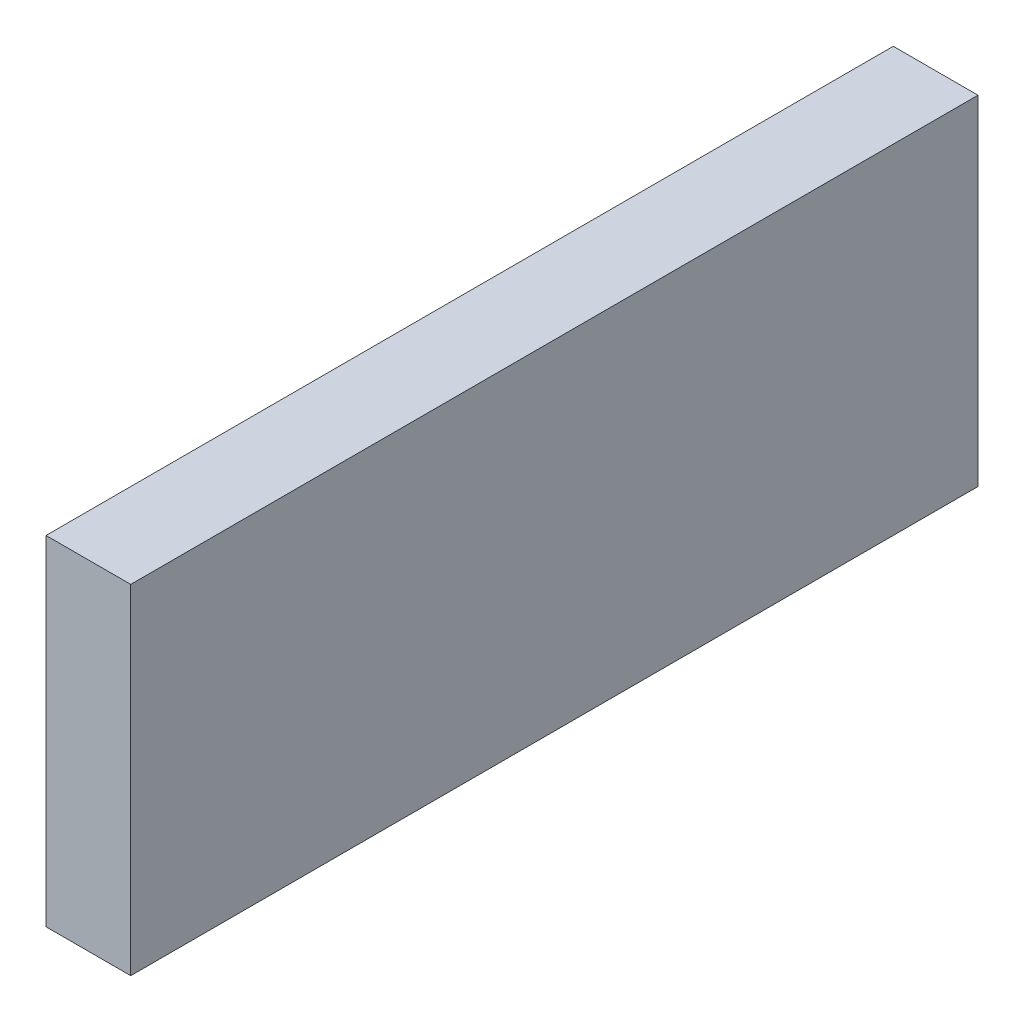
SolidWorks part; units mm, degrees
ref_plane "Front Plane" through (0, 0, 0) normal (0, 0, 1) x (1, 0, 0)
ref_plane "Top Plane" through (0, 0, 0) normal (0, 1, 0) x (1, 0, 0)
ref_plane "Right Plane" through (0, 0, 0) normal (1, 0, 0) x (0, 0, -1)
sketch "Sketch1" plane through (0, 0, 0) normal (0, 1, 0) x (1, 0, 0)
  line L1 (0, 0) -> (9.525, 0)
  line L2 (0, 0) -> (0, 95.25)
  line L3 (0, 95.25) -> (9.525, 95.25)
  line L4 (9.525, 0) -> (9.525, 95.25)
  dimension "D1" = 95.25
  dimension "D2" = 9.525
extrude "Boss-Extrude1" add sketch "Sketch1" along normal blind 38.1
